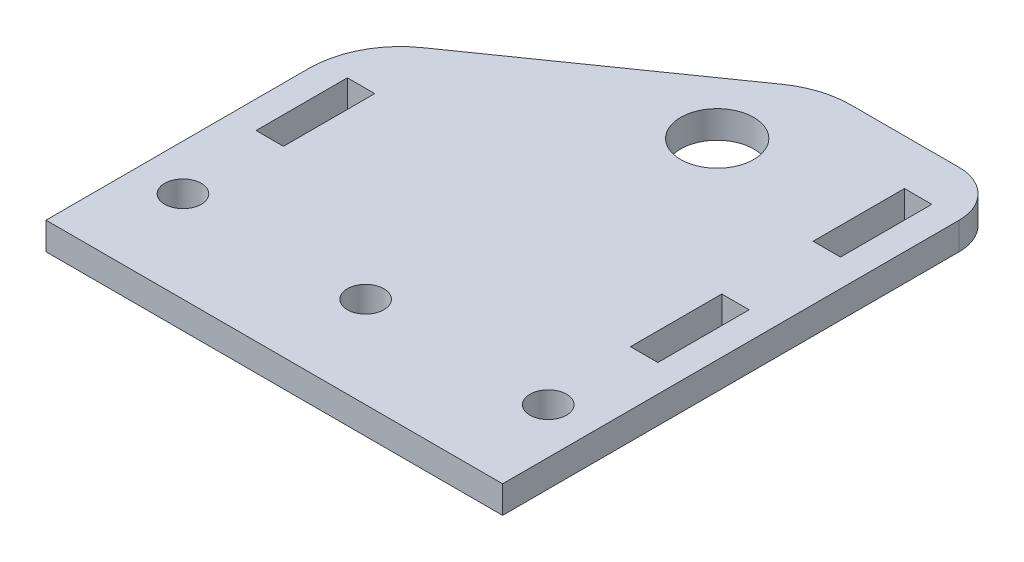
SolidWorks part; units mm, degrees
ref_plane "前视基准面" through (0, 0, 0) normal (0, 0, 1) x (1, 0, 0)
ref_plane "上视基准面" through (0, 0, 0) normal (0, 1, 0) x (1, 0, 0)
ref_plane "右视基准面" through (0, 0, 0) normal (1, 0, 0) x (0, 0, -1)
other "Configuration Table"
sketch "草图1" plane through (0, 0, 0) normal (0, 1, 0) x (1, 0, 0)
  line L1 (-25, 27.5) -> (25, 27.5)
  line L2 (-25, 27.5) -> (-25, -27.5)
  line L3 (-25, -27.5) -> (25, -27.5)
  line L4 (25, 27.5) -> (25, -27.5)
  line L5 (-25, 27.5) -> (25, -27.5) construction
  line L6 (-25, -27.5) -> (25, 27.5) construction
  point P0 (0, 0)
  dimension "D1" = 55
  dimension "D2" = 50
extrude "凸台-拉伸1" add sketch "草图1" along normal blind 3
sketch "草图2" plane through (0, 3, 0) normal (0, 1, 0) x (1, 0, 0)
  circle A0 centre (4, 17) radius 4
  dimension "D1" = 8
  dimension "D2" = 17
  dimension "D3" = 4
extrude "切除-拉伸1" cut sketch "草图2" against normal blind 3
sketch "草图3" plane through (0, 3, 0) normal (0, 1, 0) x (1, 0, 0)
  line L0 (0, -27.5) -> (0, -17.5) construction
  line L1 (-25, -27.5) -> (25, -27.5) construction
  line L2 (0, -17.5) -> (-20, -17.5) construction
  circle A0 centre (-20, -17.5) radius 2
  circle A1 centre (0, -17.5) radius 2
  circle A2 centre (20, -17.5) radius 2
  dimension "D1" = 4
  dimension "D2" = 20
  dimension "D3" = 10
extrude "切除-拉伸2" cut sketch "草图3" against normal blind 3
sketch "草图4" plane through (0, 3, 0) normal (0, 1, 0) x (1, 0, 0)
  line L6 (-22, 2.5) -> (-22, -7.5)
  line L7 (-22, 2.5) -> (-19, 2.5)
  line L8 (-19, 2.5) -> (-19, -7.5)
  line L9 (-22, -7.5) -> (-19, -7.5)
  line L10 (0, 14.8934) -> (0, -7.5) construction
  line L11 (22, -7.5) -> (19, -7.5)
  line L12 (19, 2.5) -> (19, -7.5)
  line L13 (22, 2.5) -> (19, 2.5)
  line L14 (22, 2.5) -> (22, -7.5)
  line L15 (19, 22.5) -> (19, 12.5)
  line L16 (22, 12.5) -> (19, 12.5)
  line L17 (22, 22.5) -> (22, 12.5)
  line L18 (22, 22.5) -> (19, 22.5)
  line L19 (-25, -27.5) -> (25, -27.5) construction
  dimension "D1" = 20
  dimension "D2" = 19
  dimension "D3" = 3
  dimension "D4" = 10
  dimension "D5" = 20
extrude "切除-拉伸3" cut sketch "草图4" against normal blind 3
chamfer "倒角1" distance 30 angle 35 1 edges at (-25, 1.5, -27.5)
fillet "圆角2" radius 10 2 edges at (5, 1.5, -27.5) (-25, 1.5, -6.4938)
fillet "圆角3" radius 5 1 edges at (25, 1.5, -27.5)
